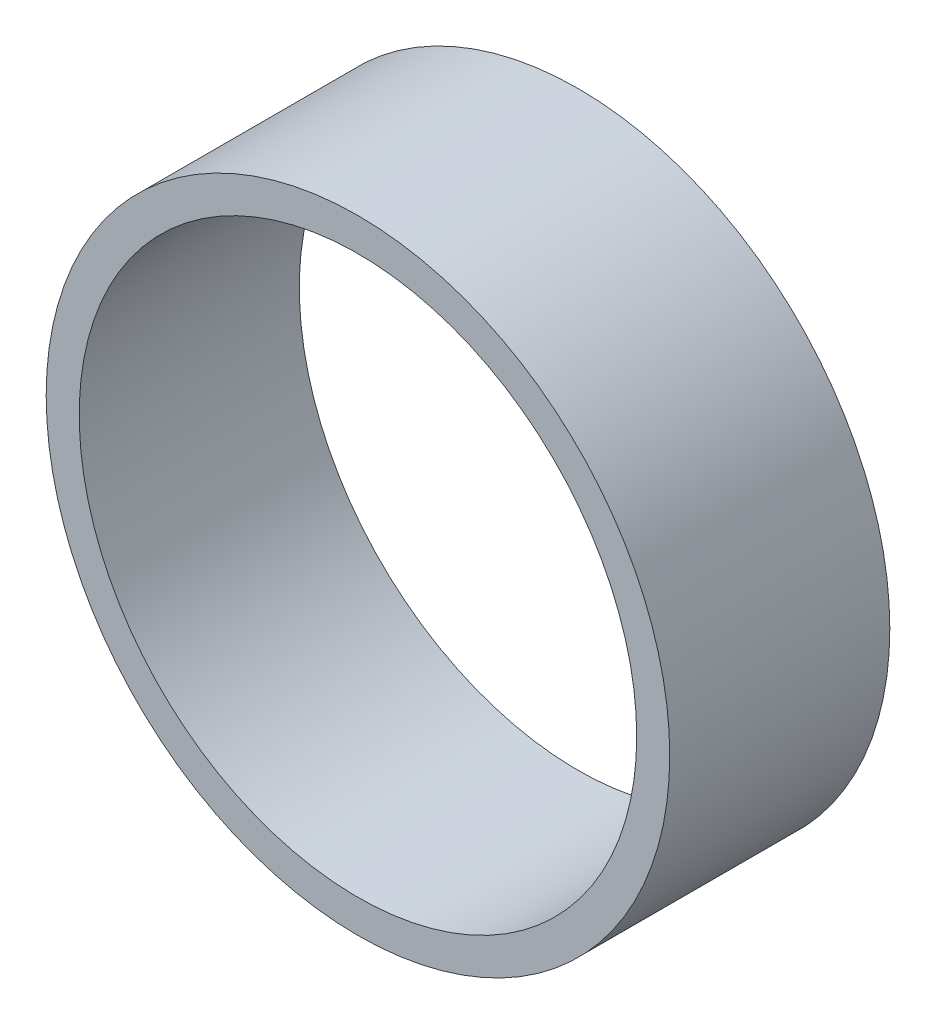
SolidWorks part; units mm, degrees
ref_plane "Front Plane" through (0, 0, 0) normal (0, 0, 1) x (1, 0, 0)
ref_plane "Top Plane" through (0, 0, 0) normal (0, 1, 0) x (1, 0, 0)
ref_plane "Right Plane" through (0, 0, 0) normal (1, 0, 0) x (0, 0, -1)
sketch "Sketch1" plane through (0, 0, 0) normal (0, 0, 1) x (1, 0, 0)
  circle A0 centre (0, 0) radius 53.975
  dimension "D1" = 107.95
extrude "Boss-Extrude1" add sketch "Sketch1" along normal blind 38.1
sketch "Sketch2" plane through (0, 0, 38.1) normal (0, 0, 1) x (1, 0, 0)
  circle A0 centre (0, 0) radius 48.26
  dimension "D1" = 96.52
extrude "Cut-Extrude1" cut sketch "Sketch2" against normal through all
